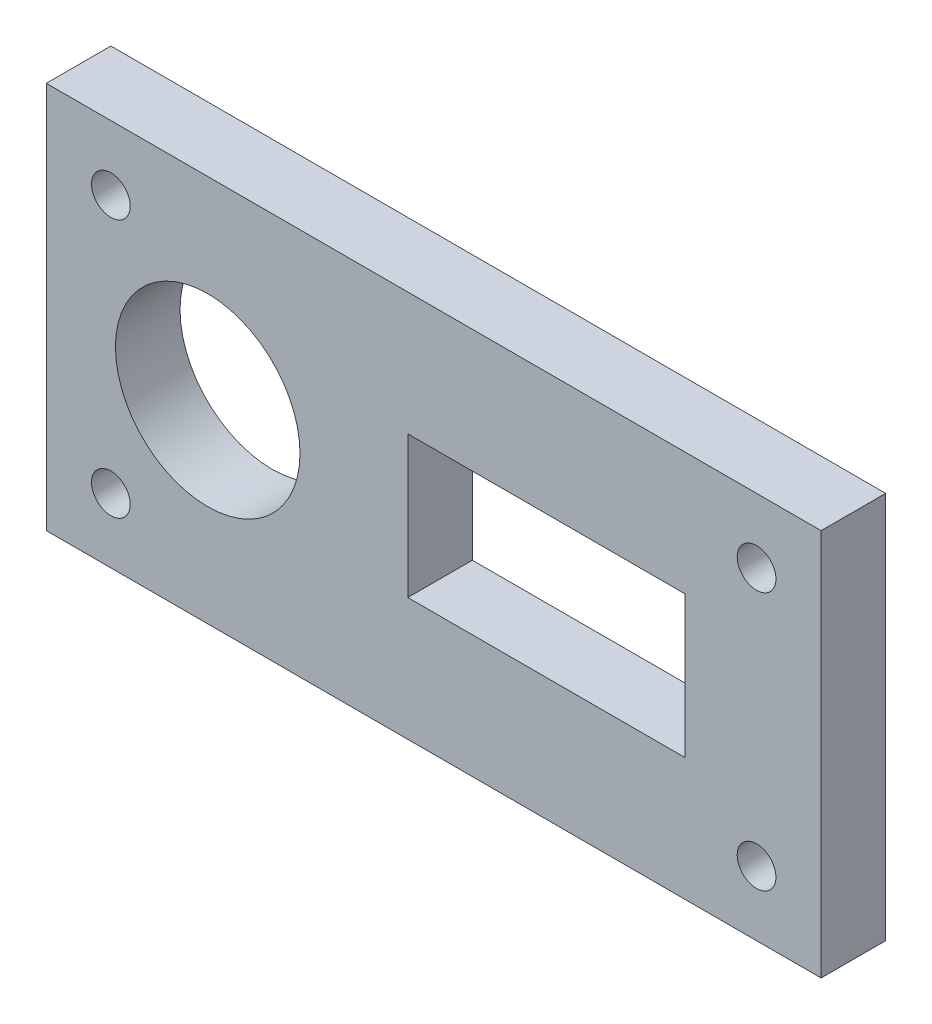
SolidWorks part; units mm, degrees
ref_plane "Alzado" through (0, 0, 0) normal (0, 0, 1) x (1, 0, 0)
ref_plane "Planta" through (0, 0, 0) normal (0, 1, 0) x (1, 0, 0)
ref_plane "Vista lateral" through (0, 0, 0) normal (1, 0, 0) x (0, 0, -1)
sketch "Croquis1" plane through (0, 0, 0) normal (0, 0, 1) x (1, 0, 0)
  line L1 (-60, -30) -> (60, -30)
  line L2 (-60, -30) -> (-60, 30)
  line L3 (-60, 30) -> (60, 30)
  line L4 (60, -30) -> (60, 30)
  line L5 (-60, -30) -> (60, 30) construction
  line L6 (-60, 30) -> (60, -30) construction
  point P0 (0, 0)
  dimension "D1" = 60
  dimension "D2" = 120
extrude "Saliente-Extruir1" add sketch "Croquis1" along normal blind 10
sketch "Croquis2" plane through (0, 0, 10) normal (0, 0, 1) x (1, 0, 0)
  line L0 (-60, 30) -> (-60, -30) construction
  circle A0 centre (-35, 0) radius 14.29
  circle A1 centre (6.9608, 0) radius 4.5
  dimension "D1" = 28.58
  dimension "D2" = 25
  dimension "D3" = 9
  dimension "D4" = 41.9608
extrude "Cortar-Extruir1" cut sketch "Croquis2" against normal through all
sketch "Croquis3" plane through (0, 0, 0) normal (0, 0, -1) x (-1, 0, 0)
  line L1 (-38.9394, -10.9786) -> (4.0178, -10.9786)
  line L2 (-38.9394, -10.9786) -> (-38.9394, 10.9786)
  line L3 (-38.9394, 10.9786) -> (4.0178, 10.9786)
  line L4 (4.0178, -10.9786) -> (4.0178, 10.9786)
  line L5 (-38.9394, -10.9786) -> (4.0178, 10.9786) construction
  line L6 (-38.9394, 10.9786) -> (4.0178, -10.9786) construction
  point P0 (-17.4608, 0)
extrude "Cortar-Extruir2" cut sketch "Croquis3" against normal through all
sketch "Croquis4" plane through (0, 0, 0) normal (0, 0, -1) x (-1, 0, 0)
  circle A0 centre (-41.8608, 5) radius 1.5
  circle A1 centre (6.9392, 5) radius 1.5
  circle A2 centre (6.9392, -5) radius 1.5
  circle A3 centre (-41.8608, -5) radius 1.5
  dimension "D1" = 3
extrude "Cortar-Extruir3" cut sketch "Croquis4" against normal blind 8
sketch "Croquis5" plane through (0, 0, 10) normal (0, 0, 1) x (1, 0, 0)
  line L0 (-60, -30) -> (60, -30) construction
  line L1 (-60, 30) -> (-100, 30)
  line L2 (-60, 30) -> (-60, -30)
  line L3 (-60, -30) -> (-100, -30)
  line L4 (-100, 30) -> (-100, -30)
  dimension "D1" = 40
extrude "Saliente-Extruir2" add sketch "Croquis5" against normal through all
sketch "Croquis6" plane through (0, 0, 10) normal (0, 0, 1) x (1, 0, 0)
  circle A0 centre (-78.2308, 0) radius 14.29
  circle A1 centre (-35, 0) radius 14.29 construction
  dimension "D1" = 28.58
  dimension "D2" = 43.2308
extrude "Cortar-Extruir4" cut sketch "Croquis6" against normal through all
sketch "Croquis7" plane through (0, 0, 10) normal (0, 0, 1) x (1, 0, 0)
  line L0 (-100, -30) -> (60, -30) construction
  line L1 (-100, 30) -> (-60, 30)
  line L2 (-100, 30) -> (-100, -30)
  line L3 (-100, -30) -> (-60, -30)
  line L4 (-60, 30) -> (-60, -30)
  line L5 (-60, -30) -> (-60, 30) construction
extrude "Cortar-Extruir5" cut sketch "Croquis7" against normal through all
sketch "Croquis8" plane through (0, 0, 0) normal (0, 0, -1) x (-1, 0, 0)
  circle A0 centre (-50, 20) radius 3
  circle A1 centre (50, 20) radius 3
  circle A2 centre (50, -20) radius 3
  circle A3 centre (-50, -20) radius 3
  dimension "D1" = 6
extrude "Cortar-Extruir6" cut sketch "Croquis8" against normal through all
